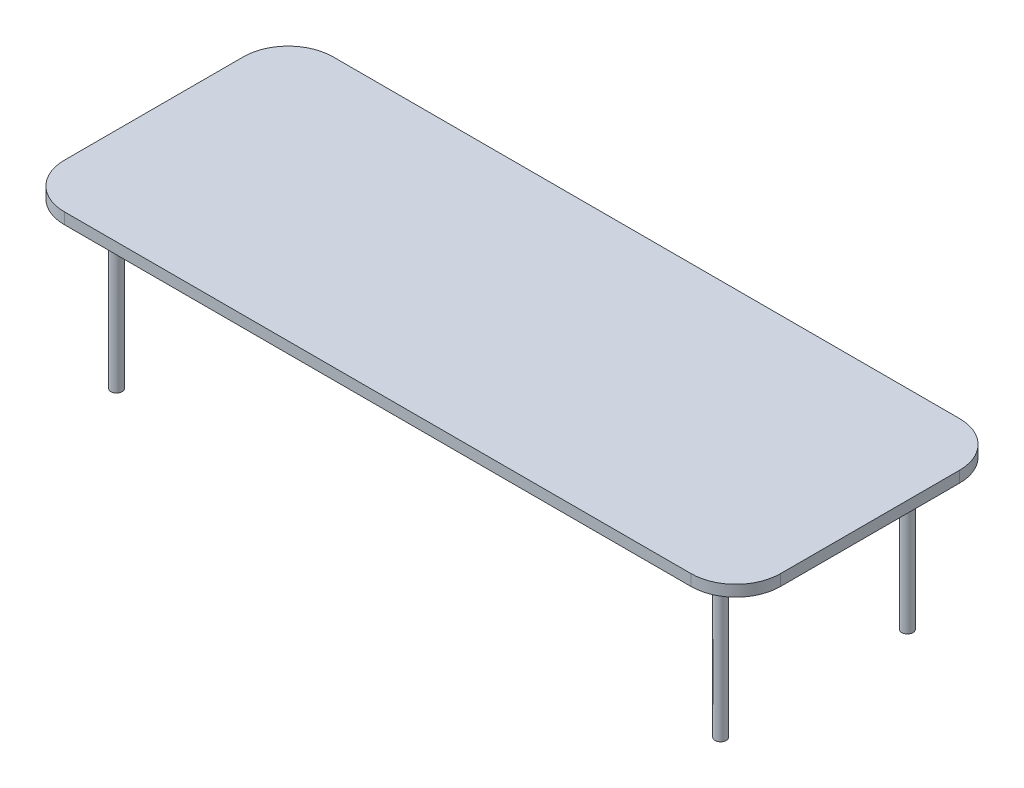
SolidWorks part; units mm, degrees
ref_plane "Front" through (0, 0, 0) normal (0, 0, 1) x (1, 0, 0)
ref_plane "Top" through (0, 0, 0) normal (0, 1, 0) x (1, 0, 0)
ref_plane "Right" through (0, 0, 0) normal (1, 0, 0) x (0, 0, -1)
sketch "Sketch1" plane through (0, 0, 0) normal (0, 1, 0) x (1, 0, 0)
  line L1 (-1422.4, 609.6) -> (1422.4, 609.6)
  line L2 (-1625.6, 406.4) -> (-1625.6, -406.4)
  line L3 (-1422.4, -609.6) -> (1422.4, -609.6)
  line L4 (1625.6, 406.4) -> (1625.6, -406.4)
  line L5 (-1625.6, 609.6) -> (1625.6, -609.6) construction
  line L6 (-1625.6, -609.6) -> (1625.6, 609.6) construction
  arc A0 (1625.6, 406.4) -> (1422.4, 609.6) centre (1422.4, 406.4) ccw
  arc A1 (1625.6, -406.4) -> (1422.4, -609.6) centre (1422.4, -406.4) cw
  arc A2 (-1422.4, -609.6) -> (-1625.6, -406.4) centre (-1422.4, -406.4) cw
  arc A3 (-1422.4, 609.6) -> (-1625.6, 406.4) centre (-1422.4, 406.4) ccw
  point P0 (0, 0)
  dimension "D3" = 203.2
  dimension "D1" = 3251.2
  dimension "D2" = 1219.2
extrude "Boss-Extrude1" add sketch "Sketch1" along normal blind 50.8
sketch "Sketch2" plane through (0, 0, 0) normal (0, -1, 0) x (1, 0, 0)
  line L1 (-1371.2445, 424.0643) -> (1371.2445, 424.0643) construction
  line L2 (-1371.2445, 424.0643) -> (-1371.2445, -424.0643) construction
  line L3 (-1371.2445, -424.0643) -> (1371.2445, -424.0643) construction
  line L4 (1371.2445, 424.0643) -> (1371.2445, -424.0643) construction
  line L5 (-1371.2445, 424.0643) -> (1371.2445, -424.0643) construction
  line L6 (-1371.2445, -424.0643) -> (1371.2445, 424.0643) construction
  circle A0 centre (-1371.2445, 424.0643) radius 25.4
  circle A1 centre (-1371.2445, -424.0643) radius 25.4
  circle A2 centre (1371.2445, -424.0643) radius 25.4
  circle A3 centre (1371.2445, 424.0643) radius 25.4
  point P0 (0, 0)
  dimension "D3" = 50.8
  dimension "D1" = 2742.489
  dimension "D2" = 848.1286
extrude "Boss-Extrude2" add sketch "Sketch2" along normal blind 711.2
